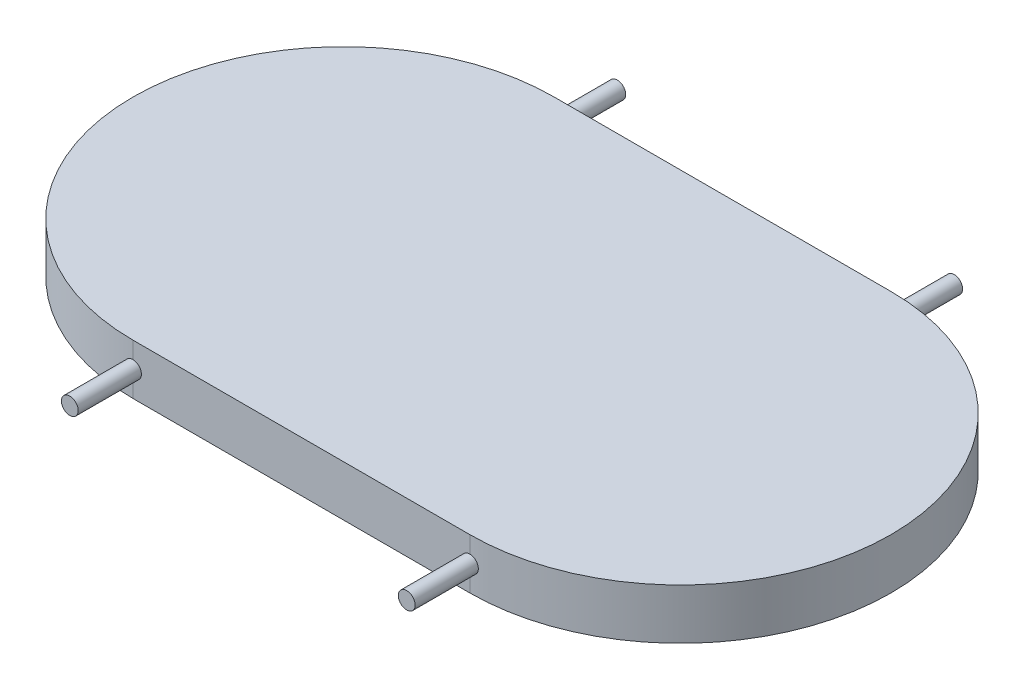
SolidWorks part; units mm, degrees
ref_plane "Front Plane" through (0, 0, 0) normal (0, 0, 1) x (1, 0, 0)
ref_plane "Top Plane" through (0, 0, 0) normal (0, 1, 0) x (1, 0, 0)
ref_plane "Right Plane" through (0, 0, 0) normal (1, 0, 0) x (0, 0, -1)
sketch "Sketch3" plane through (0, 0, 0) normal (0, 1, 0) x (1, 0, 0)
  line L0 (-200, 0) -> (200, 0) construction
  line L1 (-200, 250) -> (200, 250)
  line L2 (-200, -250) -> (200, -250)
  arc A0 (-200, 250) -> (-200, -250) centre (-200, 0) ccw
  arc A1 (200, -250) -> (200, 250) centre (200, 0) ccw
  point P2 (0, 0)
extrude "Boss-Extrude2" add sketch "Sketch3" along normal blind 60
sketch "Sketch4" plane through (0, 0, 250) normal (0, 0, 1) x (1, 0, 0)
  line L0 (-200, 60) -> (-200, 0) construction
  line L1 (200, 60) -> (200, 0) construction
  circle A0 centre (-200, 30) radius 10
  circle A1 centre (200, 30) radius 10
extrude "Boss-Extrude3" add sketch "Sketch4" along normal blind 75
sketch "Sketch5" plane through (0, 0, -250) normal (0, 0, -1) x (-1, 0, 0)
  line L0 (-200, 60) -> (-200, 0) construction
  line L1 (200, 60) -> (200, 0) construction
  circle A0 centre (-200, 30) radius 10
  circle A1 centre (200, 30) radius 10
extrude "Boss-Extrude4" add sketch "Sketch5" along normal blind 75
